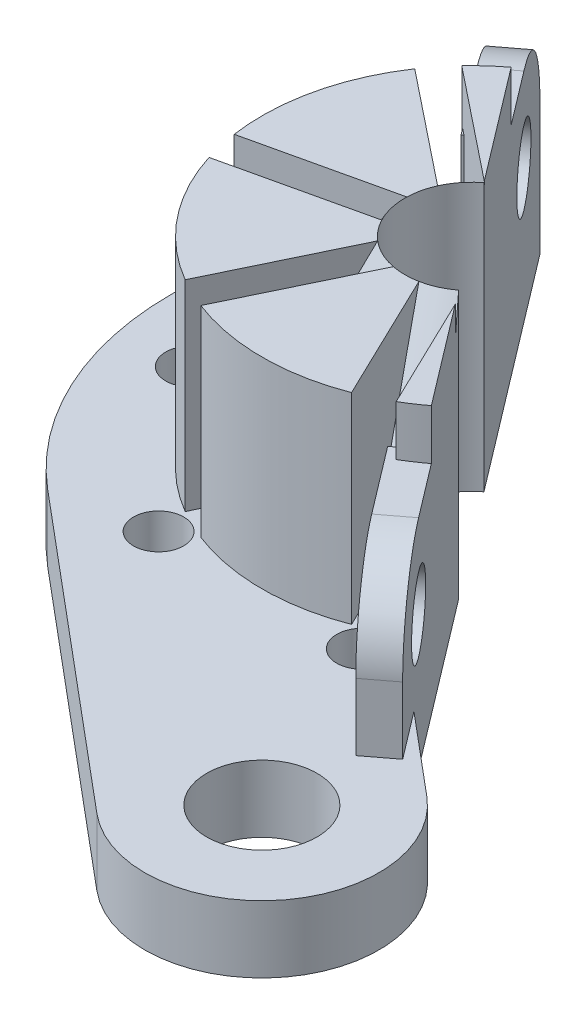
SolidWorks part; units mm, degrees
ref_plane "Front Plane" through (0, 0, 0) normal (0, 0, 1) x (1, 0, 0)
ref_plane "Top Plane" through (0, 0, 0) normal (0, 1, 0) x (1, 0, 0)
ref_plane "Right Plane" through (0, 0, 0) normal (1, 0, 0) x (0, 0, -1)
sketch "Sketch1" plane through (0, 0, 0) normal (0, 1, 0) x (1, 0, 0)
  line L0 (0, 0) -> (0, 7) construction
  circle A0 centre (0, 0) radius 1.9844
  circle A1 centre (0, 0) radius 8.9844
  circle A2 centre (0, 7) radius 0.75
  circle A3 centre (5.4728, 4.3644) radius 0.75
  circle A4 centre (6.8245, -1.5576) radius 0.75
  circle A5 centre (3.0372, -6.3068) radius 0.75
  circle A6 centre (-3.0372, -6.3068) radius 0.75
  circle A7 centre (-6.8245, -1.5576) radius 0.75
  circle A8 centre (-5.4728, 4.3644) radius 0.75
  point P20 (0, 0)
  dimension "D1" = 3.9688
  dimension "D3" = 1.5
  dimension "D4" = 7
  dimension "D2" = 7
  dimension "D5" = 7
extrude "Boss-Extrude1" add sketch "Sketch1" along normal blind 2
sketch "Sketch2" plane through (0, 2, 0) normal (0, 1, 0) x (1, 0, 0)
  line L0 (-0.5, 6.23) -> (-0.5, 1.9204)
  line L1 (0.5, 6.23) -> (0.5, 1.9204)
  line L2 (0, 0) -> (0, 7) construction
  line L3 (4.559, 4.2752) -> (1.1896, 1.5882)
  line L4 (5.1825, 3.4934) -> (1.8131, 0.8064)
  line L5 (6.185, -0.8988) -> (1.9835, 0.0601)
  line L6 (5.9625, -1.8738) -> (1.7609, -0.9148)
  line L7 (3.1536, -5.3961) -> (1.2837, -1.5132)
  line L8 (2.2526, -5.8299) -> (0.3827, -1.9471)
  line L9 (-2.2526, -5.8299) -> (-0.3827, -1.9471)
  line L10 (-3.1536, -5.3961) -> (-1.2837, -1.5132)
  line L11 (-5.9625, -1.8738) -> (-1.7609, -0.9148)
  line L12 (-6.185, -0.8988) -> (-1.9835, 0.0601)
  line L13 (-5.1825, 3.4934) -> (-1.8131, 0.8064)
  line L14 (-4.559, 4.2752) -> (-1.1896, 1.5882)
  arc A0 (-5.9625, -1.8738) -> (-3.1536, -5.3961) centre (0, 0) ccw
  circle A1 centre (0, 0) radius 1.9844 construction
  arc A2 (-1.7609, -0.9148) -> (-1.2837, -1.5132) centre (0, 0) ccw
  circle A3 centre (-6.8245, -1.5576) radius 0.75 construction
  arc A4 (-2.2526, -5.8299) -> (2.2526, -5.8299) centre (0, 0) ccw
  arc A5 (-0.3827, -1.9471) -> (0.3827, -1.9471) centre (0, 0) ccw
  arc A6 (1.2837, -1.5132) -> (1.7609, -0.9148) centre (0, 0) ccw
  arc A7 (3.1536, -5.3961) -> (5.9625, -1.8738) centre (0, 0) ccw
  arc A8 (1.9835, 0.0601) -> (1.8131, 0.8064) centre (0, 0) ccw
  arc A9 (6.185, -0.8988) -> (5.1825, 3.4934) centre (0, 0) ccw
  arc A10 (1.1896, 1.5882) -> (0.5, 1.9204) centre (0, 0) ccw
  arc A11 (4.559, 4.2752) -> (0.5, 6.23) centre (0, 0) ccw
  arc A12 (-0.5, 6.23) -> (-4.559, 4.2752) centre (0, 0) ccw
  arc A13 (-0.5, 1.9204) -> (-1.1896, 1.5882) centre (0, 0) ccw
  arc A14 (-5.1825, 3.4934) -> (-6.185, -0.8988) centre (0, 0) ccw
  arc A15 (-1.8131, 0.8064) -> (-1.9835, 0.0601) centre (0, 0) ccw
  point P37 (0, 0)
  dimension "D1" = 0.5
  dimension "D2" = 0.5
  dimension "D3" = 7
sketch "Sketch3" plane through (0, 0, 0) normal (1, 0, 0) x (0, 0, -1)
  line L0 (0, 2) -> (0, 8)
  dimension "D1" = 6
sweep "Sweep1" add profiles "Sketch2" path "Sketch3" parameters "D4"=0
sketch "Sketch4" plane through (0, 0, 0) normal (1, 0, 0) x (0, 0, -1)
  line L0 (-5.3961, 2) -> (-1.9844, 2)
  line L2 (-1.9844, 2) -> (-1.9844, 8)
  line L3 (-1.8738, 8) -> (-5.3961, 8) construction
  line L4 (-1.9844, 8) -> (-5.3961, 2)
  line L5 (0, 0) -> (0, 8) construction
  line L6 (-1.9844, 0) -> (1.9844, 0) construction
  line L7 (3.4934, 8) -> (-0.8988, 8) construction
  line L8 (-1.9844, 0) -> (1.9844, 0) construction
  line L9 (-1.9844, 0) -> (-1.9844, 2) construction
revolve "Revolve1" add sketch "Sketch4" angle 360 about L5
sketch "Sketch5" plane through (0, 2, 0) normal (0, 1, 0) x (1, 0, 0)
  line L0 (-5.4382, 7.1516) -> (5.4382, -7.1516)
  line L1 (0, 0) -> (0, 7) construction
  circle A0 centre (0, 0) radius 8.9844 construction
  dimension "D1" = 37.25
ref_plane "Plane1" through (0, 0, 0) normal (-0.796, 0, 0.6053) x (0.6053, 0, 0.796)
sketch "Sketch6" plane through (0, 0, 0) normal (-0.796, 0, 0.6053) x (0.6053, 0, 0.796)
  line L1 (-8.9844, 0) -> (8.9844, 0)
  line L2 (-8.9844, 0) -> (-8.9844, 8)
  line L3 (-8.9844, 8) -> (8.9844, 8)
  line L4 (8.9844, 0) -> (8.9844, 8)
  line L6 (2.3864, 8) -> (-2.1176, 8) construction
extrude "Cut-Extrude1" cut sketch "Sketch6" against normal through all
sketch "Sketch7" plane through (0, 2, 0) normal (0, 1, 0) x (1, 0, 0)
  line L0 (5.4382, -7.1516) -> (7.8395, -9.1658)
  line L1 (3.3409, -14.5289) -> (-5.7738, -6.8834)
  circle A0 centre (5.5902, -11.8473) radius 1.65
  arc A1 (3.3409, -14.5289) -> (7.8395, -9.1658) centre (5.5902, -11.8473) ccw
  arc A2 (-5.4382, 7.1516) -> (5.4382, -7.1516) centre (0, 0) ccw construction
  arc A3 (-5.7738, -6.8834) -> (5.4382, -7.1516) centre (0, 0) ccw
  dimension "D1" = 3.3
  dimension "D2" = 7
  dimension "D3" = 13.1
extrude "Boss-Extrude3" add sketch "Sketch7" against normal up to surface (2 mm away) up to face at (-6.8245, 0, 2.3076)
sketch "Sketch8" plane through (0, 0, 0) normal (0.796, 0, -0.6053) x (-0.6053, 0, -0.796)
  line L0 (-6.25, 2) -> (-6.25, 8) construction
  line L1 (8.9844, 2) -> (-8.9844, 2) construction
  line L2 (-10.75, 4) -> (-10.75, 2)
  line L3 (-8.25, 6.5) -> (-6.25, 6.5)
  line L5 (-10.75, 2) -> (-6.25, 2)
  line L7 (0, 0) -> (0, 8)
  line L8 (0.3377, 8) -> (-0.4275, 8) construction
  line L10 (8.4844, 2) -> (6.25, 2)
  line L11 (8.25, 6.5) -> (6.25, 6.5)
  line L12 (10.75, 4) -> (10.75, 2)
  line L14 (-6.25, 6.5) -> (-5.75, 6.5)
  line L16 (-6.9844, 2) -> (-5.75, 2)
  line L17 (-5.75, 6.5) -> (-5.75, 2)
  line L19 (10.75, 2) -> (10.75, 0)
  line L20 (10.75, 0) -> (8.9844, 0)
  line L22 (6.25, 6.5) -> (5.75, 6.5)
  line L24 (8.4844, 2) -> (5.75, 2)
  line L25 (5.75, 6.5) -> (5.75, 2)
  line L26 (8.9844, 0) -> (8.4844, 0)
  line L29 (8.4844, 0) -> (8.4844, 2)
  line L30 (-12.0412, 2) -> (-8.9844, 2) construction
  circle A0 centre (-8.25, 4) radius 1.1
  arc A2 (8.25, 6.5) -> (10.75, 4) centre (8.25, 4) cw
  arc A3 (-8.25, 6.5) -> (-10.75, 4) centre (-8.25, 4) ccw
  circle A4 centre (8.25, 4) radius 1.1
  dimension "D1" = 2.2
  dimension "D2" = 2.5
  dimension "D3" = 2
  dimension "D4" = 2
  dimension "D5" = 0.5
  dimension "D6" = 0.5
  dimension "D7" = 0.5
extrude "Boss-Extrude4" add sketch "Sketch8" against normal blind 1
